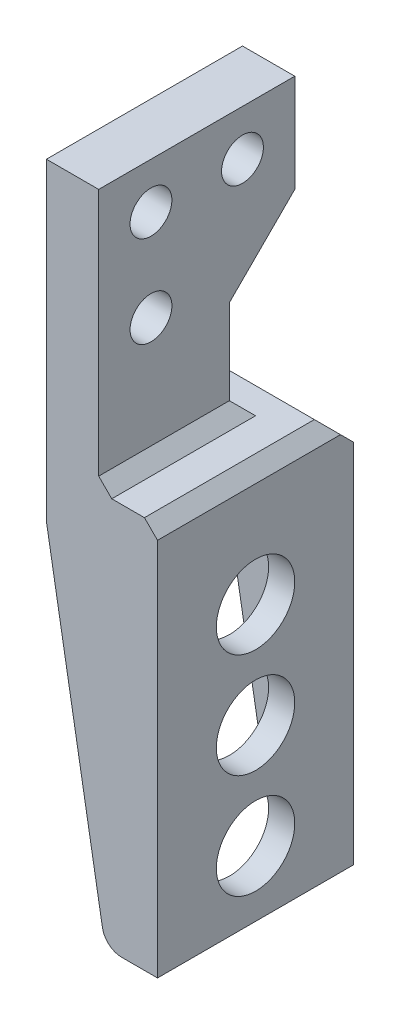
SolidWorks part; units mm, degrees
ref_plane "Płaszczyzna przednia" through (0, 0, 0) normal (0, 0, 1) x (1, 0, 0)
ref_plane "Płaszczyzna górna" through (0, 0, 0) normal (0, 1, 0) x (1, 0, 0)
ref_plane "Płaszczyzna prawa" through (0, 0, 0) normal (1, 0, 0) x (0, 0, -1)
sketch "Szkic1" plane through (0, 0, 0) normal (0, 0, 1) x (1, 0, 0)
  line L0 (0, 0) -> (4, 0)
  line L1 (4, 0) -> (4, -20)
  line L2 (4, -20) -> (8.5, -20)
  line L3 (8.5, -20) -> (8.5, -50)
  line L4 (8.5, -50) -> (4.5, -50)
  line L5 (4.5, -50) -> (0, -24)
  line L6 (0, -24) -> (0, 0)
  dimension "D1" = 50
  dimension "D2" = 4
  dimension "D3" = 8.5
  dimension "D4" = 4
  dimension "D5" = 4
  dimension "D6" = 30
extrude "Dodanie-wyciągnięcie1" add sketch "Szkic1" along normal mid plane 15
sketch "Szkic2" plane through (0, -50, 0) normal (0, -1, 0) x (1, 0, 0)
  line L0 (0, 7.5) -> (0, -7.5) construction
  line L1 (6.5, 5.5) -> (0, 5.5)
  line L2 (6.5, 5.5) -> (6.5, -5.5)
  line L3 (6.5, -5.5) -> (0, -5.5)
  line L4 (0, 5.5) -> (0, -5.5)
  line L5 (4.5, 7.5) -> (8.5, 7.5) construction
  line L6 (4.5, -7.5) -> (8.5, -7.5) construction
  line L7 (8.5, 7.5) -> (8.5, -7.5) construction
  dimension "D1" = 2
  dimension "D2" = 2
  dimension "D3" = 2
extrude "Wytnij-wyciągnięcie1" cut sketch "Szkic2" against normal up to vertex (26 mm away)
sketch "Szkic3" plane through (0, 0, 0) normal (-1, 0, 0) x (0, 0, 1)
  line L0 (-7.5, 0) -> (-7.5, -24) construction
  line L2 (-7.5, -7.5) -> (-7.5, -20)
  line L3 (-7.5, -20) -> (-2.5, -20)
  line L4 (-2.5, -12.5) -> (-2.5, -20)
  line L5 (7.5, 0) -> (-7.5, 0) construction
  line L6 (7.5, -20) -> (-7.5, -20) construction
  line L8 (-2.5, -12.5) -> (-7.5, -7.5)
  dimension "D1" = 5
  dimension "D2" = 12.5
  dimension "D3" = 45
extrude "Wytnij-wyciągnięcie2" cut sketch "Szkic3" against normal up to next
sketch "Szkic4" plane through (0, 0, 0) normal (-1, 0, 0) x (0, 0, 1)
  line L0 (-5.5, -50) -> (5.5, -50) construction
  line L1 (7.5, 0) -> (7.5, -24) construction
  line L2 (7.5, 0) -> (-7.5, 0) construction
  circle A0 centre (-3.5, -3.5) radius 1.6
  circle A1 centre (3.5, -3.5) radius 1.6
  circle A2 centre (0, -29) radius 3
  circle A3 centre (0, -37) radius 3
  circle A4 centre (0, -45) radius 3
  circle A5 centre (3.5, -10.5) radius 1.6
  point P13 (0, -50)
  point P19 (0, 0)
  dimension "D1" = 4
  dimension "D2" = 7
  dimension "D3" = 3.5
  dimension "D4" = 3.2
  dimension "D5" = 6
  dimension "D6" = 5
  dimension "D7" = 8
  dimension "D8" = 8
  dimension "D9" = 7
extrude "Wytnij-wyciągnięcie3" cut sketch "Szkic4" against normal through all
fillet "Zaokrąglenie1" radius 3 2 edges at (3.25, -24, -5.5) (3.25, -24, 5.5)
fillet "Zaokrąglenie2" radius 1.5 2 edges at (4.5, -50, 6.5) (4.5, -50, -6.5)
chamfer "Sfazowanie2" distance 1 angle 45 3 edges at (2, -20, -2.5) (4, -20, 2.5) (8.5, -20, 0)
chamfer "Sfazowanie3" distance 2 angle 45 1 edges at (3.75, -20, -7.5)
